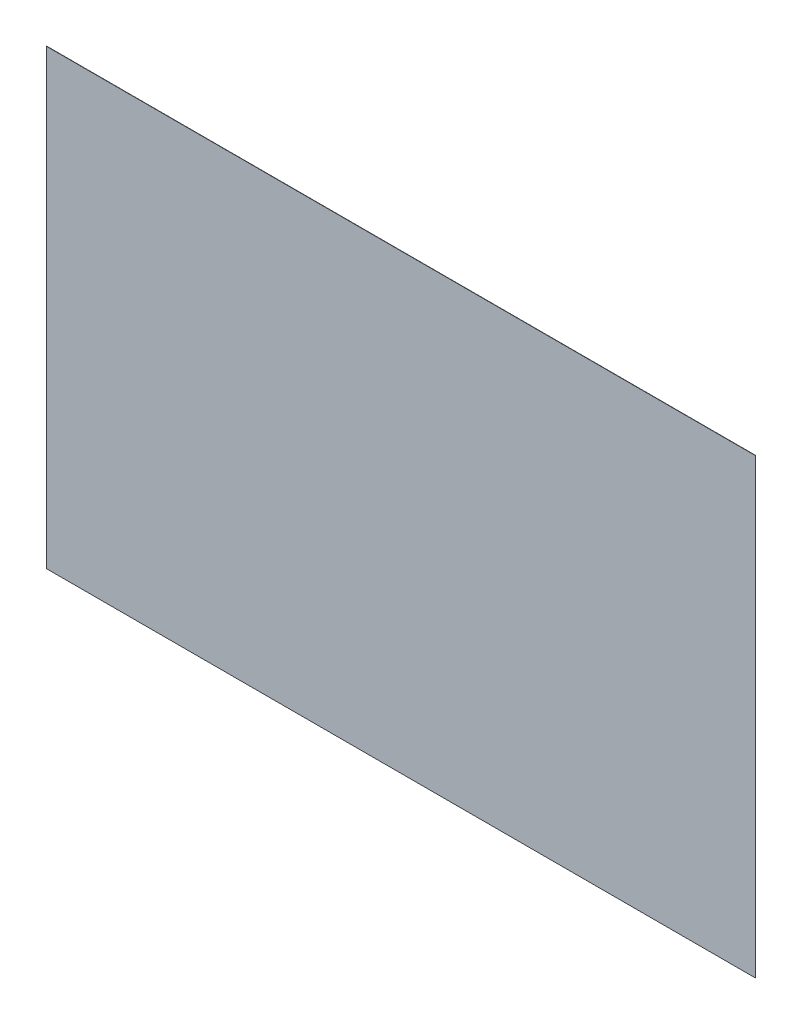
SolidWorks part; units mm, degrees
ref_plane "Front Plane" through (0, 0, 0) normal (0, 0, 1) x (1, 0, 0)
ref_plane "Top Plane" through (0, 0, 0) normal (0, 1, 0) x (1, 0, 0)
ref_plane "Right Plane" through (0, 0, 0) normal (1, 0, 0) x (0, 0, -1)
sketch "Sketch1" plane through (0, 0, 0) normal (0, 0, 1) x (1, 0, 0)
  line L1 (0, 0) -> (2500, 0)
  line L2 (0, 0) -> (0, 1595)
  line L3 (0, 1595) -> (2500, 1595)
  line L4 (2500, 0) -> (2500, 1595)
  dimension "D1" = 2500
  dimension "D2" = 1595
extrude "Boss-Extrude1" add sketch "Sketch1" along normal blind 1
